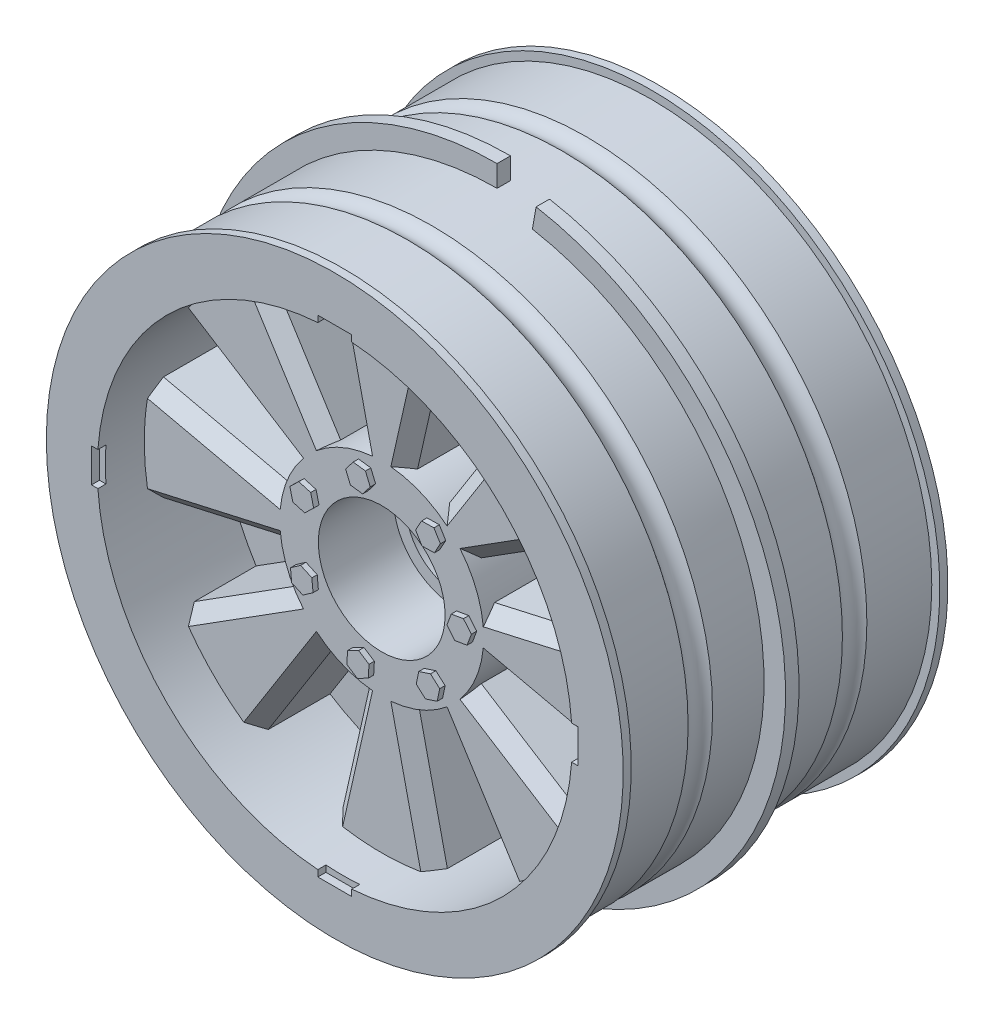
SolidWorks part; units mm, degrees
material "Chrome Stainless Steel"
ref_plane "Front Plane" through (0, 0, 0) normal (0, 0, 1) x (1, 0, 0)
ref_plane "Top Plane" through (0, 0, 0) normal (0, 1, 0) x (1, 0, 0)
ref_plane "Right Plane" through (0, 0, 0) normal (1, 0, 0) x (0, 0, -1)
sketch "Sketch1" plane through (0, 0, 0) normal (1, 0, 0) x (0, 0, -1)
  line L0 (33.1808, 0) -> (-33.1808, 0) construction
  line L1 (0, 0) -> (0, 26.543) construction
  line L2 (-14.605, 26.543) -> (-8.4605, 26.543)
  line L3 (15.367, 27.305) -> (14.605, 27.305)
  line L4 (0, 26.543) -> (0, 27.305) construction
  line L5 (14.605, 26.543) -> (14.605, 27.305)
  line L6 (-14.605, 26.543) -> (-14.605, 27.305)
  line L7 (-15.367, 27.305) -> (-15.367, 22.479)
  line L8 (-15.367, 22.479) -> (-3.81, 22.479)
  line L9 (15.367, 22.479) -> (15.367, 27.305)
  line L10 (-14.605, 27.305) -> (-15.367, 27.305)
  line L11 (-3.81, 22.479) -> (-3.81, 0)
  line L12 (-3.81, 0) -> (3.81, 0)
  line L13 (3.81, 0) -> (3.81, 22.479)
  line L14 (3.81, 22.479) -> (15.367, 22.479)
  line L15 (8.4605, 26.543) -> (14.605, 26.543)
  line L16 (0, 26.924) -> (0, 28.3552) construction
  line L17 (-6.1445, 26.543) -> (6.1445, 26.543)
  arc A1 (-8.4605, 26.543) -> (-6.1445, 26.543) centre (-7.3025, 27.305) ccw
  arc A2 (8.4605, 26.543) -> (6.1445, 26.543) centre (7.3025, 27.305) cw
  point P4 (0, 0)
  point P10 (0, 26.543)
  point P13 (0, 27.305)
  dimension "D1" = 26.543
  dimension "D2" = 29.21
  dimension "D3" = 30.734
  dimension "D4" = 27.305
  dimension "D5" = 4.064
  dimension "D6" = 3.81
  dimension "D7" = 3.81
revolve "Revolve1" add sketch "Sketch1" angle 360 about L0
sketch "Sketch2" plane through (0, 0, 0) normal (1, 0, 0) x (0, 0, -1)
  line L0 (0, 26.543) -> (0, 28.575)
  line L1 (6.1445, 26.543) -> (-6.1445, 26.543) construction
  line L2 (0, 28.575) -> (1.27, 28.575)
  line L3 (1.27, 28.575) -> (1.27, 26.543)
  line L4 (1.27, 26.543) -> (0, 26.543)
  line L5 (24.1121, 0) -> (-24.1121, 0) construction
  point P10 (0, 0)
  dimension "D1" = 1.27
  dimension "D2" = 2.032
revolve "Revolve2" add sketch "Sketch2" angle 90 about L5
sketch "Sketch3" plane through (0, 0, 0) normal (0, 1, 0) x (1, 0, 0)
  line L0 (26.543, 0) -> (26.543, -1.27)
  line L1 (26.543, -6.1445) -> (26.543, 6.1445) construction
  line L2 (26.543, -1.27) -> (28.575, -1.27)
  line L3 (28.575, -1.27) -> (28.575, 0)
  line L4 (28.575, 0) -> (26.543, 0)
  line L5 (0, 20.5013) -> (0, -20.5013) construction
  point P10 (0, 0)
  dimension "D1" = 1.27
  dimension "D2" = 2.032
revolve "Revolve3" add sketch "Sketch3" angle 80 about L5
sketch "Sketch4" plane through (0, 0, 0) normal (1, 0, 0) x (0, 0, -1)
  line L0 (0, 0) -> (-21.8548, 0)
mirror "Mirror1" about plane through (0, 0, 0) normal (0, 1, 0) of "Revolve3", "Revolve2"
sketch "Sketch5" plane through (0, 0, 3.81) normal (0, 0, 1) x (1, 0, 0)
  circle A0 centre (0, 0) radius 2.05
  dimension "D1" = 4.1
sketch "Sketch6" plane through (0, 0, -3.81) normal (0, 0, -1) x (-1, 0, 0)
  line L1 (4.2604, -5.4634) -> (6.8617, 0.958)
  line L2 (6.8617, 0.958) -> (2.6012, 6.4213)
  line L3 (2.6012, 6.4213) -> (-4.2604, 5.4634)
  line L4 (-4.2604, 5.4634) -> (-6.8617, -0.958)
  line L5 (-6.8617, -0.958) -> (-2.6012, -6.4213)
  line L6 (-2.6012, -6.4213) -> (4.2604, -5.4634)
  circle A0 centre (0, 0) radius 6 construction
  circle A1 centre (0, 0) radius 12.6656
  dimension "D1" = 12
extrude "Boss-Extrude1" add sketch "Sketch6" along normal blind 24.892
sketch "Sketch7" plane through (0, 0, -28.702) normal (0, 0, -1) x (-1, 0, 0)
  circle A0 centre (0, 0) radius 7.8375
  circle A1 centre (0, 0) radius 15.1176
extrude "Cut-Extrude1" cut sketch "Sketch5" against normal blind 53.848 contours A0
sketch "Sketch8" plane through (0, 0, 3.81) normal (0, 0, 1) x (1, 0, 0)
  line L0 (0, 22.479) -> (0, 9.6493) construction
  line L1 (2.1227, 9.4129) -> (4.9451, 21.9283)
  line L2 (-2.1227, 9.4129) -> (-4.9451, 21.9283)
  line L3 (8.157, 5.1549) -> (19.0024, 12.0089)
  line L4 (5.1549, 8.157) -> (12.0089, 19.0024)
  line L5 (9.4129, -2.1227) -> (21.9283, -4.9451)
  line L6 (9.4129, 2.1227) -> (21.9283, 4.9451)
  line L7 (5.1549, -8.157) -> (12.0089, -19.0024)
  line L8 (8.157, -5.1549) -> (19.0024, -12.0089)
  line L9 (-2.1227, -9.4129) -> (-4.9451, -21.9283)
  line L10 (2.1227, -9.4129) -> (4.9451, -21.9283)
  line L11 (-8.157, -5.1549) -> (-19.0024, -12.0089)
  line L12 (-5.1549, -8.157) -> (-12.0089, -19.0024)
  line L13 (-9.4129, 2.1227) -> (-21.9283, 4.9451)
  line L14 (-9.4129, -2.1227) -> (-21.9283, -4.9451)
  line L15 (-5.1549, 8.157) -> (-12.0089, 19.0024)
  line L16 (-8.157, 5.1549) -> (-19.0024, 12.0089)
  circle A0 centre (0, 0) radius 6
  arc A1 (-8.157, 5.1549) -> (-9.4129, 2.1227) centre (0, 0) ccw
  circle A2 centre (0, 0) radius 22.479 construction
  arc A3 (4.9451, 21.9283) -> (-4.9451, 21.9283) centre (0, 0) ccw
  arc A4 (19.0024, 12.0089) -> (12.0089, 19.0024) centre (0, 0) ccw
  arc A5 (21.9283, -4.9451) -> (21.9283, 4.9451) centre (0, 0) ccw
  arc A6 (12.0089, -19.0024) -> (19.0024, -12.0089) centre (0, 0) ccw
  arc A7 (-4.9451, -21.9283) -> (4.9451, -21.9283) centre (0, 0) ccw
  arc A8 (-19.0024, -12.0089) -> (-12.0089, -19.0024) centre (0, 0) ccw
  arc A9 (-21.9283, 4.9451) -> (-21.9283, -4.9451) centre (0, 0) ccw
  arc A10 (-12.0089, 19.0024) -> (-19.0024, 12.0089) centre (0, 0) ccw
  arc A11 (-2.1227, 9.4129) -> (-5.1549, 8.157) centre (0, 0) ccw
  arc A12 (5.1549, 8.157) -> (2.1227, 9.4129) centre (0, 0) ccw
  arc A13 (9.4129, 2.1227) -> (8.157, 5.1549) centre (0, 0) ccw
  arc A14 (8.157, -5.1549) -> (9.4129, -2.1227) centre (0, 0) ccw
  arc A15 (2.1227, -9.4129) -> (5.1549, -8.157) centre (0, 0) ccw
  arc A16 (-9.4129, -2.1227) -> (-8.157, -5.1549) centre (0, 0) ccw
  arc A17 (-5.1549, -8.157) -> (-2.1227, -9.4129) centre (0, 0) ccw
  point P43 (0, 0)
  dimension "D1" = 8
extrude "Boss-Extrude3" add sketch "Sketch8" along normal blind 7.112
sketch "Sketch9" plane through (0, 0, 10.922) normal (0, 0, 1) x (1, 0, 0)
  line L0 (4.6476, -7.2762) -> (5.7618, -6.9088)
  line L1 (8.5865, -0.903) -> (8.994, 0.1972)
  line L2 (8.994, 0.1972) -> (8.245, 1.1001)
  line L3 (8.245, 1.1001) -> (7.0885, 0.903)
  line L4 (7.0885, 0.903) -> (6.681, -0.1972)
  line L5 (6.681, -0.1972) -> (7.43, -1.1001)
  line L6 (7.43, -1.1001) -> (8.5865, -0.903)
  line L7 (5.7618, -6.9088) -> (6.0008, -5.7602)
  line L8 (6.0008, -5.7602) -> (5.1256, -4.979)
  line L9 (5.1256, -4.979) -> (4.0114, -5.3463)
  line L10 (4.0114, -5.3463) -> (3.7724, -6.4949)
  line L11 (3.7724, -6.4949) -> (4.6476, -7.2762)
  line L12 (-2.791, -8.1703) -> (-1.8091, -8.8123)
  line L13 (-1.8091, -8.8123) -> (-0.7621, -8.283)
  line L14 (-0.7621, -8.283) -> (-0.697, -7.1117)
  line L15 (-0.697, -7.1117) -> (-1.6789, -6.4696)
  line L16 (-1.6789, -6.4696) -> (-2.7259, -6.9989)
  line L17 (-2.7259, -6.9989) -> (-2.791, -8.1703)
  line L18 (-8.1279, -2.912) -> (-8.0177, -4.08)
  line L19 (-8.0177, -4.08) -> (-6.9511, -4.5685)
  line L20 (-6.9511, -4.5685) -> (-5.9947, -3.8891)
  line L21 (-5.9947, -3.8891) -> (-6.1049, -2.7211)
  line L22 (-6.1049, -2.7211) -> (-7.1715, -2.2326)
  line L23 (-7.1715, -2.2326) -> (-8.1279, -2.912)
  line L24 (-7.3444, 4.5391) -> (-8.1888, 3.7247)
  line L25 (-8.1888, 3.7247) -> (-7.9058, 2.5862)
  line L26 (-7.9058, 2.5862) -> (-6.7783, 2.262)
  line L27 (-6.7783, 2.262) -> (-5.9338, 3.0764)
  line L28 (-5.9338, 3.0764) -> (-6.2168, 4.2149)
  line L29 (-6.2168, 4.2149) -> (-7.3444, 4.5391)
  line L30 (-1.0303, 8.5721) -> (-2.1936, 8.7246)
  line L31 (-2.1936, 8.7246) -> (-2.9072, 7.7934)
  line L32 (-2.9072, 7.7934) -> (-2.4577, 6.7098)
  line L33 (-2.4577, 6.7098) -> (-1.2944, 6.5573)
  line L34 (-1.2944, 6.5573) -> (-0.5808, 7.4885)
  line L35 (-0.5808, 7.4885) -> (-1.0303, 8.5721)
  line L36 (6.0595, 6.1502) -> (5.4535, 7.1547)
  line L37 (5.4535, 7.1547) -> (4.2805, 7.1321)
  line L38 (4.2805, 7.1321) -> (3.7136, 6.105)
  line L39 (3.7136, 6.105) -> (4.3197, 5.1005)
  line L40 (4.3197, 5.1005) -> (5.4926, 5.1231)
  line L41 (5.4926, 5.1231) -> (6.0595, 6.1502)
  circle A0 centre (7.8375, 0) radius 1.016 construction
  circle A1 centre (0, 0) radius 7.8375 construction
  point P49 (0, 0)
  dimension "D1" = 2.032
extrude "Boss-Extrude4" add sketch "Sketch9" along normal blind 0.508
chamfer "Chamfer1" distance 1.27 angle 45 1 edges at (13.5797, 8.5819, 10.922)
chamfer "Chamfer2" distance 1.27 angle 45 15 edges at (13.5797, -8.5819, 10.922) (8.5819, -13.5797, 10.922) (3.5339, -15.6706, 10.922) (-3.5339, -15.6706, 10.922) (-8.5819, -13.5797, 10.922) (-13.5797, -8.5819, 10.922) (-15.6706, -3.5339, 10.922) (-15.6706, 3.5339, 10.922) (-13.5797, 8.5819, 10.922) (-8.5819, 13.5797, 10.922) (-3.5339, 15.6706, 10.922) (8.5819, 13.5797, 10.922) (3.5339, 15.6706, 10.922) (15.6706, 3.5339, 10.922) (15.6706, -3.5339, 10.922)
sketch "Sketch12" plane through (0, 0, -3.81) normal (0, 0, -1) x (-1, 0, 0)
  circle A0 centre (0, 0) radius 2.05
  circle A1 centre (0, 0) radius 5.9309
extrude "Boss-Extrude5" add sketch "Sketch12" along normal blind 13.97
sketch "Sketch13" plane through (0, 0, 3.81) normal (0, 0, 1) x (1, 0, 0)
  circle A0 centre (0, 0) radius 4.832
extrude "Cut-Extrude2" cut sketch "Sketch13" against normal blind 8.382
extrude "Cut-Extrude3" cut sketch "Sketch7" against normal blind 9.906
fillet "Fillet1" radius 2.54 1 edges at (-7.8375, 0, -18.796)
sketch "Sketch14" plane through (0, 0, 15.367) normal (0, 0, 1) x (1, 0, 0)
  line L0 (23.0286, 1.6011) -> (21.9294, 1.6011)
  line L1 (-1.6011, 23.0286) -> (1.6011, 23.0286)
  line L2 (-1.6011, 23.0286) -> (-1.6011, 21.9294)
  line L3 (-1.6011, 21.9294) -> (1.6011, 21.9294)
  line L4 (1.6011, 23.0286) -> (1.6011, 21.9294)
  line L5 (-1.6011, 23.0286) -> (1.6011, 21.9294) construction
  line L6 (-1.6011, 21.9294) -> (1.6011, 23.0286) construction
  line L7 (23.0286, 1.6011) -> (23.0286, -1.6011)
  line L8 (23.0286, -1.6011) -> (21.9294, -1.6011)
  line L9 (21.9294, 1.6011) -> (21.9294, -1.6011)
  line L10 (1.6011, -23.0286) -> (1.6011, -21.9294)
  line L11 (1.6011, -23.0286) -> (-1.6011, -23.0286)
  line L12 (-1.6011, -23.0286) -> (-1.6011, -21.9294)
  line L13 (1.6011, -21.9294) -> (-1.6011, -21.9294)
  line L14 (-23.0286, -1.6011) -> (-21.9294, -1.6011)
  line L15 (-23.0286, -1.6011) -> (-23.0286, 1.6011)
  line L16 (-23.0286, 1.6011) -> (-21.9294, 1.6011)
  line L17 (-21.9294, -1.6011) -> (-21.9294, 1.6011)
  circle A0 centre (0, 0) radius 22.479 construction
  point P2 (0, 22.479)
  point P22 (0, 0)
  dimension "D1" = 4
extrude "Cut-Extrude4" cut sketch "Sketch14" against normal blind 0.762
